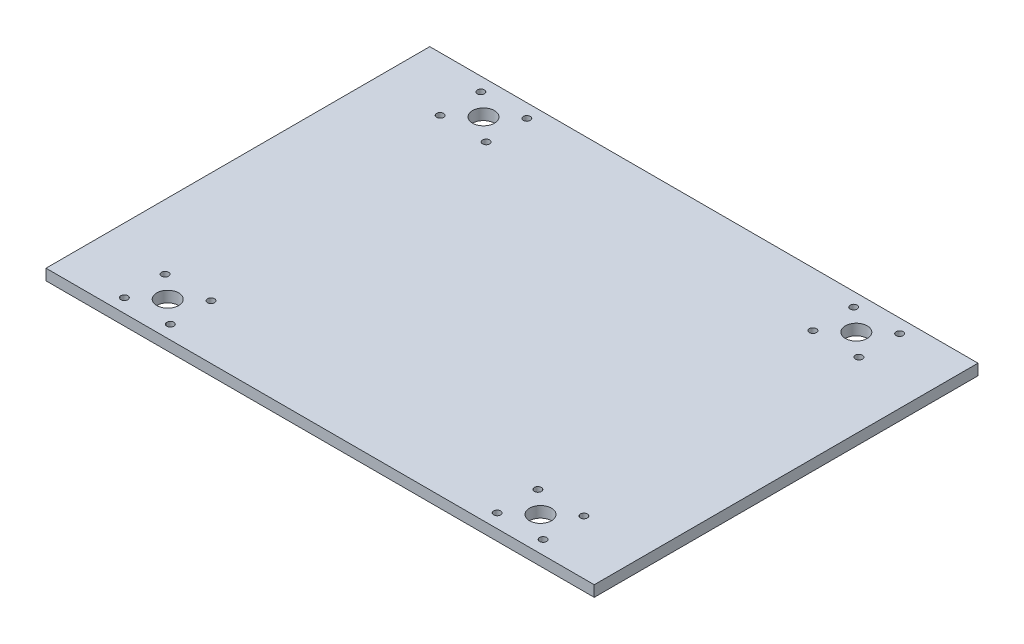
SolidWorks part; units mm, degrees
ref_plane "Plan de face" through (0, 0, 0) normal (0, 0, 1) x (1, 0, 0)
ref_plane "Plan de dessus" through (0, 0, 0) normal (0, 1, 0) x (1, 0, 0)
ref_plane "Plan de droite" through (0, 0, 0) normal (1, 0, 0) x (0, 0, -1)
sketch "Esquisse1" plane through (0, 0, 0) normal (0, 1, 0) x (1, 0, 0)
  line L0 (-125, 0) -> (125, 0) construction
  line L1 (-70, 87.5) -> (45, 87.5)
  line L2 (-125, 67.5) -> (-125, -67.5)
  line L3 (-70, -87.5) -> (45, -87.5)
  line L4 (125, 42.5) -> (125, -42.5)
  line L5 (-125, 87.5) -> (125, -87.5) construction
  line L6 (-125, -87.5) -> (125, 87.5) construction
  line L23 (-70, -87.5) -> (45, -87.5)
  line L24 (-125, 67.5) -> (-125, 87.5)
  line L25 (-125, 87.5) -> (-70, 87.5)
  line L26 (45, 87.5) -> (125, 87.5)
  line L27 (125, 87.5) -> (125, 42.5)
  line L28 (125, -42.5) -> (125, -87.5)
  line L29 (125, -87.5) -> (45, -87.5)
  line L30 (-125, -67.5) -> (-125, -87.5)
  line L31 (-125, -87.5) -> (-70, -87.5)
  point P0 (0, 0)
  dimension "D1" = 250
  dimension "D4" = 175
extrude "Boss.-Extru.1" add sketch "Esquisse1" along normal blind 5
sketch "Esquisse2" plane through (0, 5, 0) normal (0, 1, 0) x (1, 0, 0)
  line L1 (125, 87.5) -> (125, -87.5) construction
  line L2 (67.5, -72) -> (102.5, -72) construction
  line L3 (85, 87.5) -> (85, -87.5) construction
  line L4 (67.5, -56.5) -> (102.5, -56.5)
  line L5 (67.5, -56.5) -> (67.5, -87.5)
  line L6 (-125, 87.5) -> (125, 87.5) construction
  line L11 (-125, -87.5) -> (125, -87.5) construction
  line L13 (0, 87.5) -> (0, -87.5) construction
  line L14 (-125, 87.5) -> (125, 87.5) construction
  line L15 (-125, -87.5) -> (125, -87.5) construction
  line L16 (-125, 0) -> (125, 0) construction
  line L17 (-125, 87.5) -> (-125, -87.5) construction
  line L18 (125, 87.5) -> (125, -87.5) construction
  line L19 (-85, 87.5) -> (-85, -87.5) construction
  line L20 (-125, 87.5) -> (-125, -87.5) construction
  line L21 (67.5, -87.5) -> (102.5, -87.5)
  line L22 (102.5, -56.5) -> (102.5, -87.5)
  line L23 (67.5, -56.5) -> (102.5, -87.5) construction
  line L24 (67.5, -87.5) -> (102.5, -56.5) construction
  circle A0 centre (85, -72) radius 5
  circle A1 centre (95.4802, -81.2825) radius 1.6
  circle A2 centre (95.4802, -62.7175) radius 1.6
  circle A3 centre (74.5198, -81.2825) radius 1.6
  circle A4 centre (74.5198, -62.7175) radius 1.6
  point P12 (85, -72)
  dimension "D3" = 31
  dimension "D4" = 35
  dimension "D5" = 3.2
  dimension "D6" = 10
  dimension "D1" = 40
  dimension "D2" = 40
  dimension "D7" = 14
extrude "Enlèv. mat.-Extru.4" cut sketch "Esquisse2" against normal blind 10 contours A0 | A4 | A3 | A1 | A2
mirror "Symétrie1" about plane through (0, 0, 0) normal (0, 0, 1) of "Enlèv. mat.-Extru.4"
mirror "Symétrie2" about plane through (0, 0, 0) normal (1, 0, 0) of "Enlèv. mat.-Extru.4", "Symétrie1"
